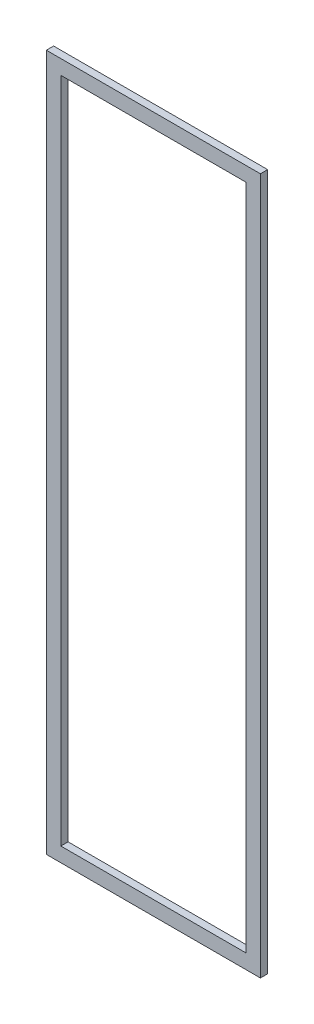
SolidWorks part; units mm, degrees
ref_plane "Alzado" through (0, 0, 0) normal (0, 0, 1) x (1, 0, 0)
ref_plane "Planta" through (0, 0, 0) normal (0, 1, 0) x (1, 0, 0)
ref_plane "Vista lateral" through (0, 0, 0) normal (1, 0, 0) x (0, 0, -1)
sketch "Croquis1" plane through (0, 0, 0) normal (0, 0, 1) x (1, 0, 0)
  line L0 (50.8, -50.8) -> (699.2, -50.8)
  line L1 (0, 0) -> (750, 0)
  line L2 (0, 0) -> (0, -2440)
  line L3 (0, -2440) -> (750, -2440)
  line L4 (750, 0) -> (750, -2440)
  line L5 (699.2, -50.8) -> (699.2, -2389.2)
  line L6 (50.8, -2389.2) -> (699.2, -2389.2)
  line L7 (50.8, -50.8) -> (50.8, -2389.2)
  dimension "D1" = 750
  dimension "D2" = 2440
  dimension "D3" = 50.8
extrude "Saliente-Extruir1" add sketch "Croquis1" along normal blind 25.4
